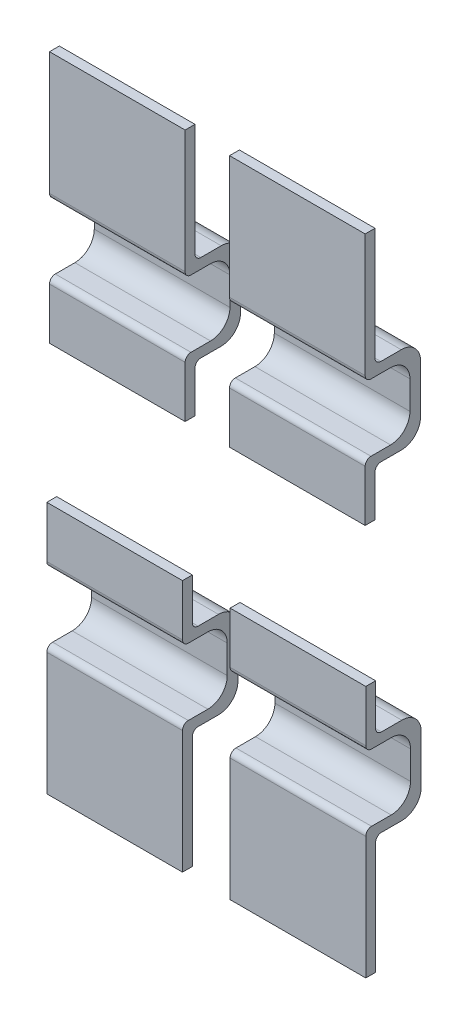
SolidWorks part; units mm, degrees
material "黄铜"
ref_plane "前视基准面" through (0, 0, 0) normal (0, 0, 1) x (1, 0, 0)
ref_plane "上视基准面" through (0, 0, 0) normal (0, 1, 0) x (1, 0, 0)
ref_plane "右视基准面" through (0, 0, 0) normal (1, 0, 0) x (0, 0, -1)
sketch "草图1" plane through (0, 0, 0) normal (1, 0, 0) x (0, 0, -1)
  line L0 (5.5709, 32.4762) -> (5.5709, 26.6739)
  line L1 (5.8709, 26.3739) -> (6.922, 26.3739)
  line L2 (7.922, 25.3739) -> (7.922, 22.8831)
  line L3 (6.922, 21.8831) -> (5.8709, 21.8831)
  line L4 (5.5709, 21.5831) -> (5.5709, 20.4666)
  line L5 (5.5709, 20.4666) -> (5.5709, 19.7556)
  line L6 (5.5709, 19.7556) -> (5.5709, 19.445)
  line L7 (5.5709, 19.445) -> (5.0622, 19.445)
  line L8 (5.0622, 19.445) -> (5.0622, 22.0918)
  line L9 (5.0622, 22.2887) -> (5.0622, 22.3918)
  line L14 (6.3727, 25.8461) -> (5.3622, 25.8461)
  line L15 (5.0622, 26.1461) -> (5.0622, 32.4762)
  line L16 (5.0622, 32.4762) -> (5.5709, 32.4762)
  line L17 (7.3727, 24.8461) -> (7.3727, 23.3918)
  line L18 (6.3727, 22.3918) -> (5.3622, 22.3918)
  arc A0 (6.922, 21.8831) -> (7.922, 22.8831) centre (6.922, 22.8831) ccw
  arc A1 (6.3727, 25.8461) -> (7.3727, 24.8461) centre (6.3727, 24.8461) cw
  arc A2 (7.922, 25.3739) -> (6.922, 26.3739) centre (6.922, 25.3739) ccw
  arc A3 (7.3727, 23.3918) -> (6.3727, 22.3918) centre (6.3727, 23.3918) cw
  arc A4 (5.5709, 26.6739) -> (5.8709, 26.3739) centre (5.8709, 26.6739) ccw
  arc A5 (5.0622, 26.1461) -> (5.3622, 25.8461) centre (5.3622, 26.1461) ccw
  arc A6 (5.5709, 21.5831) -> (5.8709, 21.8831) centre (5.8709, 21.5831) cw
  arc A7 (5.0622, 22.0918) -> (5.3622, 22.3918) centre (5.3622, 22.0918) cw
  dimension "D1" = 1
  dimension "D2" = 1
  dimension "D3" = 0.3
extrude "凸台-拉伸1" add sketch "草图1" along normal blind 7 contours A7 L8 L7 L6 L5 L4 A6 L3 A0 L2 A2 L1 A4 L0 L16 L15 A5 L14 A1 L17 A3 L18
move or copy body "实体-移动/复制3" bodies to move or copy 106 copy no translate (7.1557, 0, 0)
move or copy body "实体-移动/复制4" bodies to move or copy 109 copy yes number of copies 1 translate (9.2909, 0, 0)
move or copy body "实体-移动/复制5" bodies to move or copy 109 copy yes number of copies 1 translate (-0.1375, -16.5308, 0)
move or copy body "实体-移动/复制9" bodies to move or copy 111 copy no rotation origin (10.5182, 9.4298, 0) rotation axis (0, 0, 1) rotation angle 180
move or copy body "实体-移动/复制10" bodies to move or copy 115 copy no translate (0, -3.6759, 0)
move or copy body "实体-移动/复制11" bodies to move or copy 116 copy yes number of copies 1 translate (9.4587, 0, 0)
